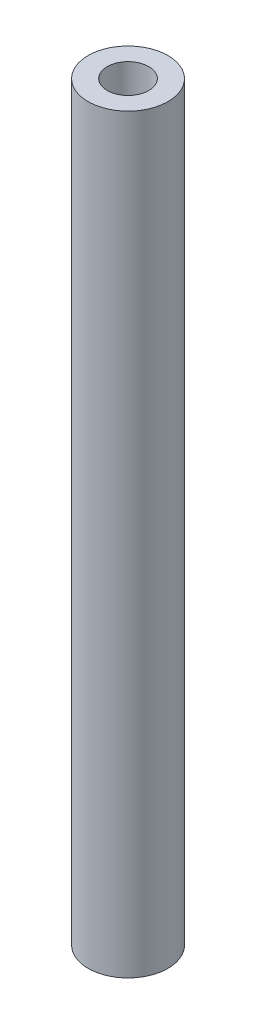
SolidWorks part; units mm, degrees
ref_plane "Front Plane" through (0, 0, 0) normal (0, 0, 1) x (1, 0, 0)
ref_plane "Top Plane" through (0, 0, 0) normal (0, 1, 0) x (1, 0, 0)
ref_plane "Right Plane" through (0, 0, 0) normal (1, 0, 0) x (0, 0, -1)
sketch "Sketch1" plane through (0, 0, 0) normal (0, 1, 0) x (1, 0, 0)
  circle A0 centre (0, 0) radius 3.25
  circle A1 centre (0, 0) radius 6.25
  dimension "D1" = 12.5
  dimension "D2" = 6.5
extrude "Boss-Extrude1" add sketch "Sketch1" along normal blind 117.5 contours A1 | A0
